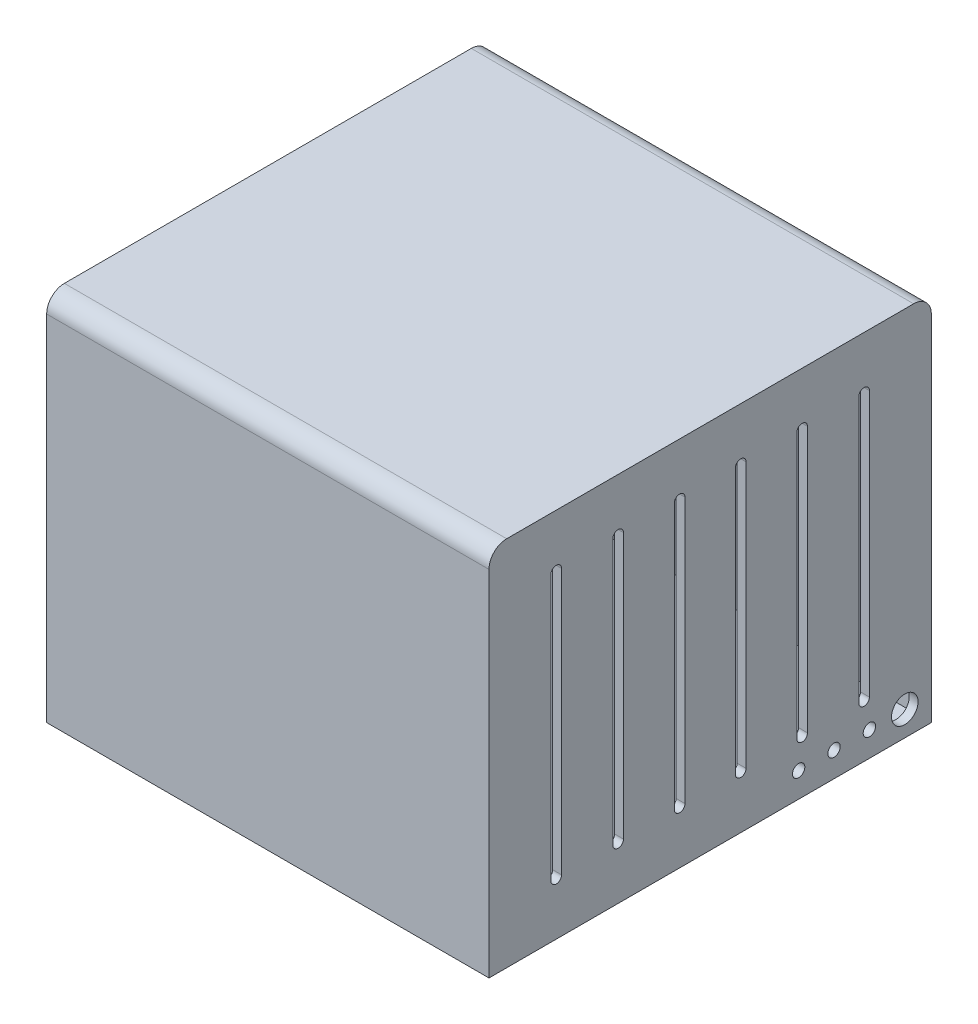
SolidWorks part; units mm, degrees
ref_plane "Front Plane" through (0, 0, 0) normal (0, 0, 1) x (1, 0, 0)
ref_plane "Top Plane" through (0, 0, 0) normal (0, 1, 0) x (1, 0, 0)
ref_plane "Right Plane" through (0, 0, 0) normal (1, 0, 0) x (0, 0, -1)
sketch "Sketch1" plane through (0, 0, 0) normal (0, 1, 0) x (1, 0, 0)
  line L1 (-62.5, 62.5) -> (62.5, 62.5)
  line L2 (-62.5, 62.5) -> (-62.5, -62.5)
  line L3 (-62.5, -62.5) -> (62.5, -62.5)
  line L4 (62.5, 62.5) -> (62.5, -62.5)
  line L5 (-62.5, 62.5) -> (62.5, -62.5) construction
  line L6 (-62.5, -62.5) -> (62.5, 62.5) construction
  point P0 (0, 0)
extrude "Boss-Extrude1" add sketch "Sketch1" along normal blind 2.5
sketch "Sketch2" plane through (0, 0, 62.5) normal (0, 0, 1) x (1, 0, 0)
  line L1 (62.5, 2.5) -> (-62.5, 2.5)
  line L2 (62.5, 2.5) -> (62.5, 102.5)
  line L3 (62.5, 102.5) -> (-62.5, 102.5)
  line L4 (-62.5, 2.5) -> (-62.5, 102.5)
sketch "Sketch3" plane through (0, 0, -62.5) normal (0, 0, -1) x (-1, 0, 0)
  line L1 (-62.5, 2.5) -> (62.5, 2.5)
  line L2 (-62.5, 2.5) -> (-62.5, 102.5)
  line L3 (-62.5, 102.5) -> (62.5, 102.5)
  line L4 (62.5, 2.5) -> (62.5, 102.5)
extrude "Boss-Extrude3" add sketch "Sketch3" against normal blind 2.5
extrude "Boss-Extrude4" add sketch "Sketch2" against normal blind 2.5
sketch "Sketch5" plane through (62.5, 0, 0) normal (1, 0, 0) x (0, 0, -1)
  line L1 (62.5, 102.5) -> (-62.5, 102.5)
  line L2 (62.5, 102.5) -> (62.5, 0)
  line L3 (62.5, 0) -> (-62.5, 0)
  line L4 (-62.5, 102.5) -> (-62.5, 0)
extrude "Boss-Extrude6" add sketch "Sketch5" against normal blind 2.5
sketch "Sketch11" plane through (0, 2.5, 0) normal (0, 1, 0) x (1, 0, 0)
  line L1 (50, 51.5) -> (58, 51.5)
  line L2 (50, 51.5) -> (50, 50)
  line L3 (50, 50) -> (58, 50)
  line L4 (58, 51.5) -> (58, 50)
extrude "Boss-Extrude9" add sketch "Sketch11" along normal blind 3
mirror "Mirror6" about plane through (0, 0, 0) normal (0, 0, 1) of "Boss-Extrude9"
sketch "Sketch12" plane through (0, 0, -50) normal (0, 0, 1) x (1, 0, 0)
  line L0 (58, 5.5) -> (58, 2.5) construction
  line L1 (50, 5.5) -> (58, 5.5)
  line L2 (50, 5.5) -> (50, 4)
  line L3 (50, 4) -> (58, 4)
  line L4 (58, 5.5) -> (58, 4)
extrude "Boss-Extrude10" add sketch "Sketch12" along normal blind 4.5
mirror "Mirror7" about plane through (0, 0, 0) normal (0, 0, 1) of "Boss-Extrude10"
mirror "Mirror8" about plane through (0, 0, 0) normal (1, 0, 0) of "Boss-Extrude9"
mirror "Mirror9" about plane through (0, 0, 0) normal (1, 0, 0) of "Boss-Extrude10"
mirror "Mirror10" about plane through (0, 0, 0) normal (0, 0, 1) of "Mirror8"
mirror "Mirror11" about plane through (0, 0, 0) normal (0, 0, 1) of "Mirror9"
sketch "Sketch13" plane through (62.5, 0, -52.869) normal (1, 0, 0) x (0, 0, -1)
  line L1 (-60, 90) -> (-63, 90)
  line L2 (-60, 90) -> (-60, 15)
  line L3 (-60, 15) -> (-63, 15)
  line L4 (-63, 90) -> (-63, 15)
extrude "Cut-Extrude3" cut sketch "Sketch13" against normal blind 4.5
sketch "Sketch15" plane through (62.5, 0, 0) normal (1, 0, 0) x (0, 0, -1)
  line L1 (-45, 90) -> (-42, 90)
  line L2 (-45, 90) -> (-45, 15)
  line L3 (-45, 15) -> (-42, 15)
  line L4 (-42, 90) -> (-42, 15)
extrude "Cut-Extrude4" cut sketch "Sketch15" against normal blind 4.5
sketch "Sketch17" plane through (62.5, 0, 0) normal (1, 0, 0) x (0, 0, -1)
  line L1 (-27.5, 90) -> (-24.5, 90)
  line L2 (-27.5, 90) -> (-27.5, 15)
  line L3 (-27.5, 15) -> (-24.5, 15)
  line L4 (-24.5, 90) -> (-24.5, 15)
extrude "Cut-Extrude5" cut sketch "Sketch17" against normal blind 4.5
mirror "Mirror12" about plane through (0, 0, 0) normal (0, 0, 1) of "Cut-Extrude5"
mirror "Mirror13" about plane through (0, 0, 0) normal (0, 0, 1) of "Cut-Extrude4"
mirror "Mirror14" about plane through (0, 0, 0) normal (0, 0, 1) of "Cut-Extrude3"
sketch "Sketch18" plane through (62.5, 0, 0) normal (1, 0, 0) x (0, 0, -1)
  line L0 (-7.131, 90) -> (-10.131, 90) construction
  circle A0 centre (-8.631, 90) radius 1.5
extrude "Cut-Extrude6" cut sketch "Sketch18" against normal blind 4.5
sketch "Sketch19" plane through (62.5, 0, 0) normal (1, 0, 0) x (0, 0, -1)
  line L0 (-10.131, 15) -> (-7.131, 15) construction
  circle A0 centre (-8.631, 15) radius 1.5
extrude "Cut-Extrude7" cut sketch "Sketch19" against normal blind 4.5
sketch "Sketch20" plane through (62.5, 0, 0) normal (1, 0, 0) x (0, 0, -1)
  line L0 (-45, 15) -> (-42, 15) construction
  circle A0 centre (-43.5, 15) radius 1.5
sketch "Sketch21" plane through (62.5, 0, 0) normal (1, 0, 0) x (0, 0, -1)
  line L0 (-27.5, 15) -> (-24.5, 15) construction
  circle A0 centre (-26, 15) radius 1.5
extrude "Cut-Extrude8" cut sketch "Sketch21" against normal blind 4.5
extrude "Cut-Extrude9" cut sketch "Sketch20" against normal blind 4.5
mirror "Mirror15" about plane through (0, 0, 0) normal (0, 0, 1) of "Cut-Extrude7"
mirror "Mirror16" about plane through (0, 0, 0) normal (0, 0, 1) of "Cut-Extrude9"
mirror "Mirror17" about plane through (0, 0, 0) normal (0, 0, 1) of "Cut-Extrude8"
sketch "Sketch22" plane through (62.5, 0, 0) normal (1, 0, 0) x (0, 0, -1)
  line L0 (-42, 90) -> (-45, 90) construction
  circle A0 centre (-43.5, 90) radius 1.5
extrude "Cut-Extrude10" cut sketch "Sketch22" against normal blind 4.5
sketch "Sketch23" plane through (62.5, 0, 0) normal (1, 0, 0) x (0, 0, -1)
  line L0 (-24.5, 90) -> (-27.5, 90) construction
  circle A0 centre (-26, 90) radius 1.5
extrude "Cut-Extrude11" cut sketch "Sketch23" against normal blind 4.5
mirror "Mirror18" about plane through (0, 0, 0) normal (0, 0, 1) of "Cut-Extrude10"
mirror "Mirror19" about plane through (0, 0, 0) normal (0, 0, 1) of "Cut-Extrude6"
mirror "Mirror20" about plane through (0, 0, 0) normal (0, 0, 1) of "Cut-Extrude11"
sketch "Sketch24" plane through (0, 102.5, 0) normal (0, 1, 0) x (1, 0, 0)
  line L1 (62.5, 62.5) -> (-62.5, 62.5)
  line L2 (62.5, 62.5) -> (62.5, -62.5)
  line L3 (62.5, -62.5) -> (-62.5, -62.5)
  line L4 (-62.5, 62.5) -> (-62.5, -62.5)
extrude "Boss-Extrude11" add sketch "Sketch24" along normal blind 2.5
sketch "Sketch25" plane through (-62.5, 0, 0) normal (-1, 0, 0) x (0, 0, 1)
  line L1 (-52.5, 105) -> (-62.5, 105)
  line L2 (-52.5, 105) -> (-52.5, 95)
  line L3 (-52.5, 95) -> (-62.5, 95)
  line L4 (-62.5, 105) -> (-62.5, 95)
extrude "Boss-Extrude12" add sketch "Sketch25" against normal blind 2.5
mirror "Mirror21" about plane through (0, 0, 0) normal (0, 0, 1) of "Boss-Extrude12"
sketch "Sketch26" plane through (-62.5, 0, 0) normal (-1, 0, 0) x (0, 0, 1)
  line L1 (-62.5, 0) -> (-52.5, 0)
  line L2 (-62.5, 0) -> (-62.5, 10)
  line L3 (-62.5, 10) -> (-52.5, 10)
  line L4 (-52.5, 0) -> (-52.5, 10)
extrude "Boss-Extrude13" add sketch "Sketch26" against normal blind 2.5
mirror "Mirror22" about plane through (0, 0, 0) normal (0, 0, 1) of "Boss-Extrude13"
sketch "Sketch27" plane through (-62.5, 0, 0) normal (-1, 0, 0) x (0, 0, 1)
  circle A0 centre (-56.5, 99) radius 1.5
extrude "Cut-Extrude12" cut sketch "Sketch27" against normal blind 2.5
mirror "Mirror23" about plane through (0, 0, 0) normal (0, 0, 1) of "Cut-Extrude12"
sketch "Sketch28" plane through (-62.5, 0, 0) normal (-1, 0, 0) x (0, 0, 1)
  circle A0 centre (-56.5, 6) radius 1.5
extrude "Cut-Extrude13" cut sketch "Sketch28" against normal blind 2.5
mirror "Mirror24" about plane through (0, 0, 0) normal (0, 0, 1) of "Cut-Extrude13"
sketch "Sketch29" plane through (62.5, 0, 0) normal (1, 0, 0) x (0, 0, -1)
  circle A0 centre (25, 7) radius 1.75
  point P2 (0, 0)
sketch "Sketch31" plane through (62.5, 0, 0) normal (1, 0, 0) x (0, 0, -1)
  circle A0 centre (35, 7) radius 1.75
extrude "Cut-Extrude14" cut sketch "Sketch31" against normal blind 10
extrude "Cut-Extrude15" cut sketch "Sketch29" against normal blind 10
sketch "Sketch32" plane through (62.5, 0, 0) normal (1, 0, 0) x (0, 0, -1)
  circle A0 centre (45, 7) radius 1.75
  point P2 (0, 0)
extrude "Cut-Extrude16" cut sketch "Sketch32" against normal blind 10
fillet "Fillet1" radius 5 1 edges at (0, 105, 62.5)
fillet "Fillet2" radius 5 1 edges at (0, 105, -62.5)
sketch "Sketch33" plane through (62.5, 0, 0) normal (1, 0, 0) x (0, 0, -1)
  circle A0 centre (55, 7) radius 3.75
extrude "Cut-Extrude17" cut sketch "Sketch33" against normal blind 10
